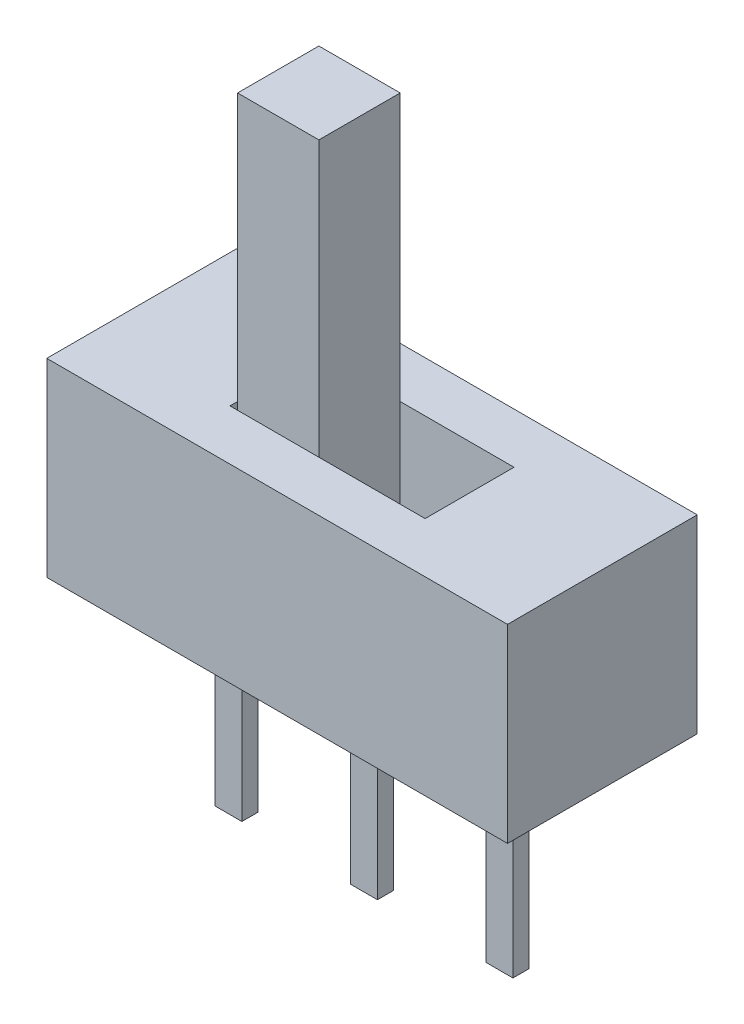
SolidWorks part; units mm, degrees
ref_plane "Front Plane" through (0, 0, 0) normal (0, 0, 1) x (1, 0, 0)
ref_plane "Top Plane" through (0, 0, 0) normal (0, 1, 0) x (1, 0, 0)
ref_plane "Right Plane" through (0, 0, 0) normal (1, 0, 0) x (0, 0, -1)
sketch "Sketch1" plane through (0, 0, 0) normal (0, 1, 0) x (1, 0, 0)
  line L1 (-4.25, 1.75) -> (4.25, 1.75)
  line L2 (-4.25, 1.75) -> (-4.25, -1.75)
  line L3 (-4.25, -1.75) -> (4.25, -1.75)
  line L4 (4.25, 1.75) -> (4.25, -1.75)
  line L5 (0, -1.75) -> (0, 1.75) construction
  line L6 (-4.25, 0) -> (4.25, 0) construction
  point P0 (0, 0)
  dimension "D1" = 8.5
  dimension "D2" = 3.5
extrude "Boss-Extrude1" add sketch "Sketch1" along normal blind 3.5
sketch "Sketch2" plane through (0, 3.5, 0) normal (0, 1, 0) x (1, 0, 0)
  line L0 (0, -2.975) -> (0, 2.975) construction
  line L1 (-1.8, 0.82) -> (1.8, 0.82)
  line L2 (-1.8, 0.82) -> (-1.8, -0.82)
  line L3 (-1.8, -0.82) -> (1.8, -0.82)
  line L4 (1.8, 0.82) -> (1.8, -0.82)
  line L5 (-4.675, 0) -> (4.675, 0) construction
  point P0 (0, 0.82)
  point P6 (-1.8, 0)
  dimension "D1" = 1.64
  dimension "D2" = 3.6
extrude "Cut-Extrude1" cut sketch "Sketch2" against normal blind 2
sketch "Sketch3" plane through (0, 1.5, 0) normal (0, 1, 0) x (1, 0, 0)
  line L0 (-4.675, 0) -> (4.675, 0) construction
  line L5 (-1.73, 0.75) -> (-0.23, 0.75)
  line L6 (-1.73, 0.75) -> (-1.73, -0.75)
  line L7 (-1.73, -0.75) -> (-0.23, -0.75)
  line L8 (-0.23, 0.75) -> (-0.23, -0.75)
  line L9 (-0.98, -0.75) -> (-0.98, 0.75) construction
  line L10 (-1.73, 0) -> (-0.23, 0) construction
  line L13 (-1.73, 0.75) -> (-1.8, 0.75) construction
  line L15 (-1.8, 0.82) -> (-1.8, -0.82) construction
  line L16 (-1.73, 0.75) -> (-1.73, 0.82) construction
  line L17 (-1.8, 0.82) -> (1.8, 0.82) construction
  point P0 (-0.98, 0)
  dimension "D1" = 1.5
extrude "Boss-Extrude3" add sketch "Sketch3" along normal offset from surface (7 mm away) 5 up to face at (0, 3.5, 0) offset beyond the face yes
sketch "Sketch4" plane through (0, 0, 0) normal (0, -1, 0) x (1, 0, 0)
  line L1 (-0.25, 0.15) -> (0.25, 0.15)
  line L2 (-0.25, 0.15) -> (-0.25, -0.15)
  line L3 (-0.25, -0.15) -> (0.25, -0.15)
  line L4 (0.25, 0.15) -> (0.25, -0.15)
  line L5 (0, -0.15) -> (0, 0.15) construction
  line L6 (-0.25, 0) -> (0.25, 0) construction
  point P0 (0, 0)
  dimension "D1" = 0.5
  dimension "D2" = 0.3
extrude "Boss-Extrude4" add sketch "Sketch4" along normal blind 3.7
pattern_linear "LPattern1" count 2 spacing 2.5 along (1, 0, 0) count 2 spacing 2.5 along (-1, 0, 0) of "Boss-Extrude4"
equation "\"D1@Boss-Extrude3\" = 2 + 5.5"
